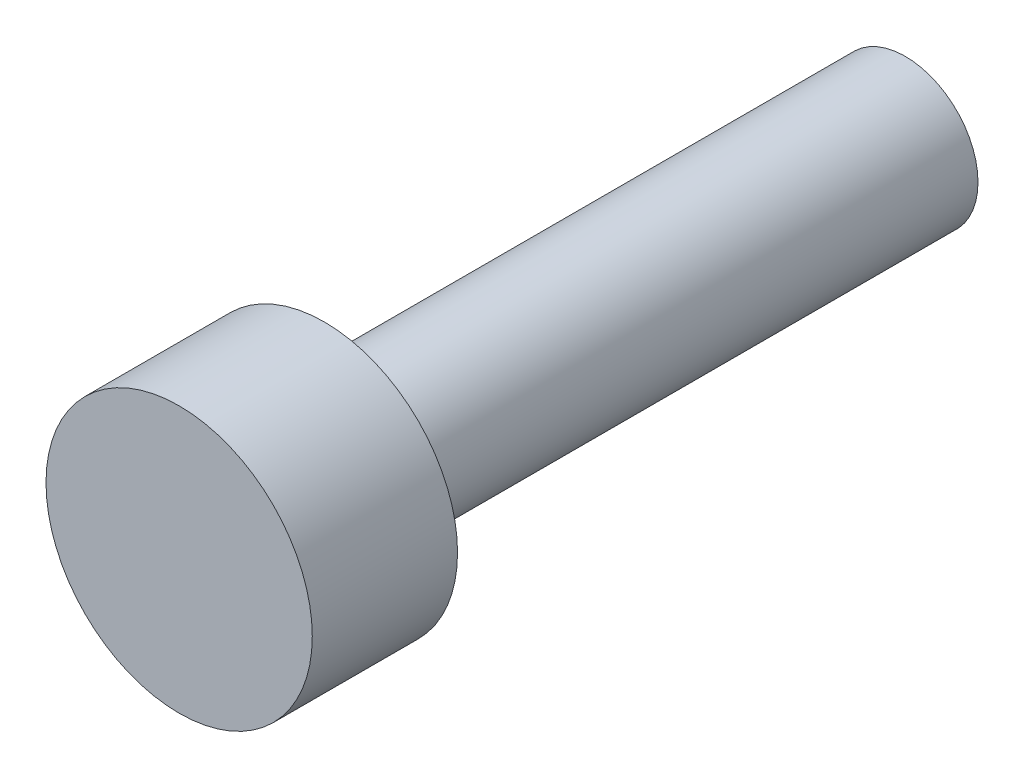
SolidWorks part; units mm, degrees
ref_plane "Front Plane" through (0, 0, 0) normal (0, 0, 1) x (1, 0, 0)
ref_plane "Top Plane" through (0, 0, 0) normal (0, 1, 0) x (1, 0, 0)
ref_plane "Right Plane" through (0, 0, 0) normal (1, 0, 0) x (0, 0, -1)
sketch "Shank_nominal_thread_envelope_profile" plane through (0, 0, 0) normal (0, 0, 1) x (1, 0, 0)
  circle A0 centre (0, 0) radius 1.5
  dimension "D1" = 3
extrude "Shank_nominal_thread_envelope" add sketch "Shank_nominal_thread_envelope_profile" along normal blind 12 from offset 12
sketch "Socket_head_envelope_profile" plane through (0, 0, 0) normal (0, 0, 1) x (1, 0, 0)
  circle A0 centre (0, 0) radius 2.75
  dimension "D1" = 5.5
extrude "Socket_head_envelope" add sketch "Socket_head_envelope_profile" along normal blind 3
